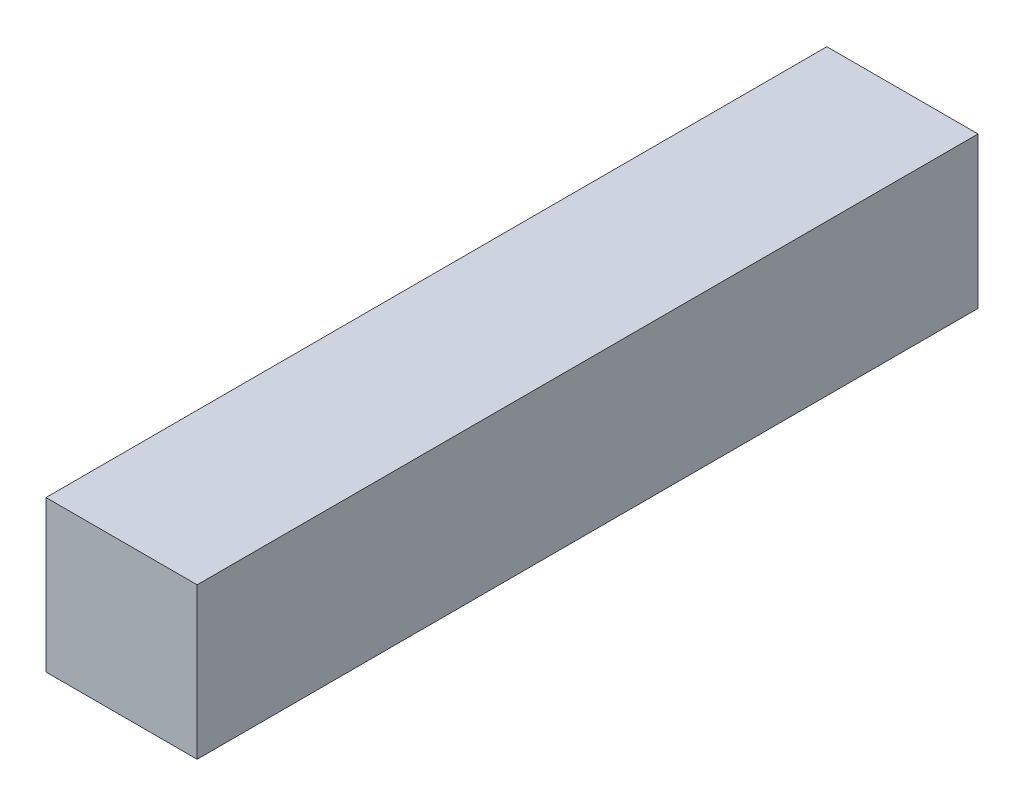
SolidWorks part; units mm, degrees
ref_plane "Front Plane" through (0, 0, 0) normal (0, 0, 1) x (1, 0, 0)
ref_plane "Top Plane" through (0, 0, 0) normal (0, 1, 0) x (1, 0, 0)
ref_plane "Right Plane" through (0, 0, 0) normal (1, 0, 0) x (0, 0, -1)
sketch "Sketch1" plane through (0, 0, 0) normal (0, 1, 0) x (1, 0, 0)
  line L1 (-38.1, -196.85) -> (38.1, -196.85)
  line L2 (-38.1, -196.85) -> (-38.1, 196.85)
  line L3 (-38.1, 196.85) -> (38.1, 196.85)
  line L4 (38.1, -196.85) -> (38.1, 196.85)
  line L5 (-38.1, -196.85) -> (38.1, 196.85) construction
  line L6 (-38.1, 196.85) -> (38.1, -196.85) construction
  point P0 (0, 0)
  dimension "D1" = 393.7
  dimension "D2" = 76.2
extrude "Boss-Extrude1" add sketch "Sketch1" along normal blind 76.2
